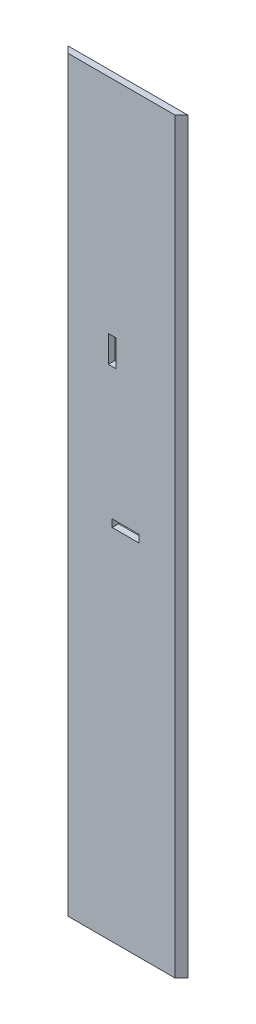
SolidWorks part; units mm, degrees
material "Balsa"
ref_plane "Front Plane" through (0, 0, 0) normal (1, 0, 0) x (0, 1, 0)
ref_plane "Top Plane" through (0, 0, 0) normal (0, 0, 1) x (0, 1, 0)
ref_plane "Right Plane" through (0, 0, 0) normal (0, 1, 0) x (-1, 0, 0)
sketch "Sketch1" plane through (0, 0, 0) normal (0, 0, 1) x (0, 1, 0)
  line L1 (-175, -25) -> (175, -25)
  line L2 (-175, -25) -> (-175, 25)
  line L3 (-175, 25) -> (175, 25)
  line L4 (175, -25) -> (175, 25)
  line L5 (-175, -25) -> (175, 25) construction
  line L6 (-175, 25) -> (175, -25) construction
  point P0 (0, 0)
  dimension "D1" = 50
  dimension "D2" = 350
extrude "Boss-Extrude1" add sketch "Sketch1" along normal blind 3
sketch "Sketch2" plane through (0, -175, 0) normal (0, -1, 0) x (1, 0, 0)
  line L0 (-25, 3) -> (-25, 0)
  line L1 (-25, 0) -> (-28, 0)
  line L2 (-25, 3) -> (-28, 0)
  line L3 (0, 0) -> (0, 3) construction
  line L4 (-25, 3) -> (25, 3) construction
  line L5 (25, 3) -> (28, 0)
  line L6 (25, 0) -> (28, 0)
  line L7 (25, 3) -> (25, 0)
  dimension "D1" = 45
extrude "Boss-Extrude2" add sketch "Sketch2" against normal through all
sketch "Sketch3" plane through (0, 0, 0) normal (0, 0, -1) x (1, 0, 0)
  line L4 (-28, -175) -> (28, -175)
  line L5 (28, -175) -> (28, 175)
  line L6 (28, 175) -> (-28, 175)
  line L7 (-28, 175) -> (-28, -175)
  line L8 (-28, -175) -> (28, -175)
  line L9 (28, -175) -> (28, 175)
  line L10 (28, 175) -> (-28, 175)
  line L11 (-28, 175) -> (-28, -175)
  line L24 (28, 0) -> (-28, 0) construction
  line L25 (-4.4619, 3.5) -> (8.0381, 3.5)
  line L26 (-4.4619, 3.5) -> (-4.4619, 7)
  line L27 (-4.4619, 7) -> (8.0381, 7)
  line L28 (8.0381, 3.5) -> (8.0381, 7)
  line L29 (-6.1908, -70.8074) -> (-6.1908, -58.3074)
  line L30 (-6.1908, -70.8074) -> (-2.6908, -70.8074)
  line L31 (-2.6908, -70.8074) -> (-2.6908, -58.3074)
  line L32 (-6.1908, -58.3074) -> (-2.6908, -58.3074)
  dimension "D1" = 0
extrude "Cut-Extrude2" cut sketch "Sketch3" against normal through all flip side to cut
